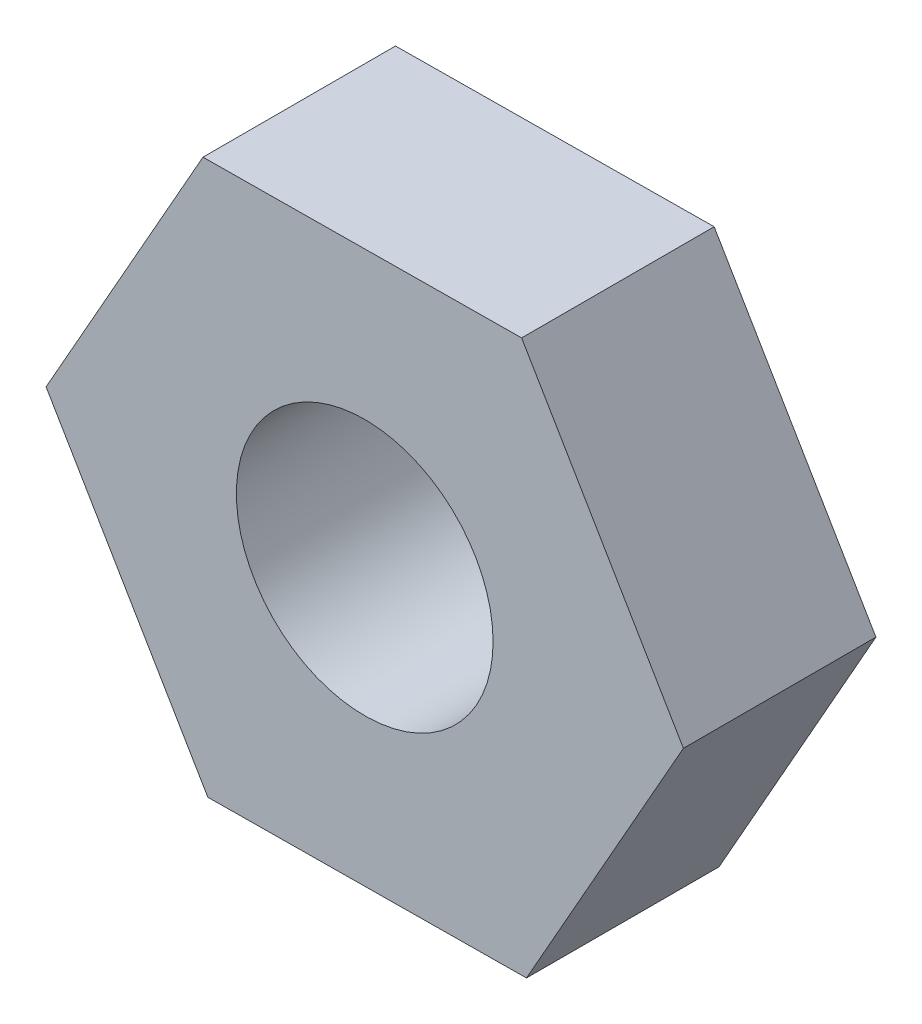
SolidWorks part; units mm, degrees
ref_plane "前视基准面" through (0, 0, 0) normal (0, 0, 1) x (1, 0, 0)
ref_plane "上视基准面" through (0, 0, 0) normal (0, 1, 0) x (1, 0, 0)
ref_plane "右视基准面" through (0, 0, 0) normal (1, 0, 0) x (0, 0, -1)
sketch "草图1" plane through (0, 0, 0) normal (0, 0, 1) x (1, 0, 0)
  line L1 (1.2602, -2.139) -> (2.4825, 0.0219)
  line L2 (2.4825, 0.0219) -> (1.2223, 2.1608)
  line L3 (1.2223, 2.1608) -> (-1.2602, 2.139)
  line L4 (-1.2602, 2.139) -> (-2.4825, -0.0219)
  line L5 (-2.4825, -0.0219) -> (-1.2223, -2.1608)
  line L6 (-1.2223, -2.1608) -> (1.2602, -2.139)
  circle A0 centre (0, 0) radius 2.15 construction
  circle A1 centre (0, 0) radius 1
extrude "凸台-拉伸1" add sketch "草图1" along normal blind 1.5
